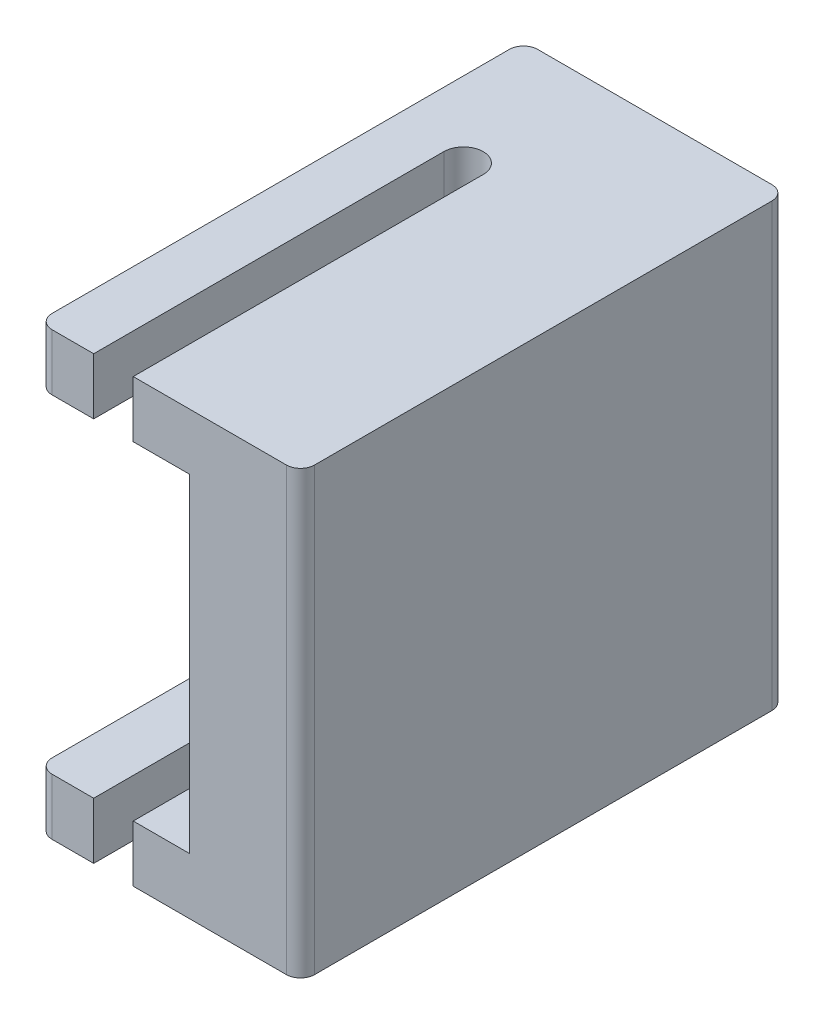
SolidWorks part; units mm, degrees
ref_plane "Front Plane" through (0, 0, 0) normal (0, 0, 1) x (1, 0, 0)
ref_plane "Top Plane" through (0, 0, 0) normal (0, 1, 0) x (1, 0, 0)
ref_plane "Right Plane" through (0, 0, 0) normal (1, 0, 0) x (0, 0, -1)
sketch "Sketch1" plane through (0, 0, 0) normal (0, 0, 1) x (1, 0, 0)
  line L0 (-46.5, 39.0875) -> (-46.5, 29.0875)
  line L1 (-46.5, 29.0875) -> (-19.625, 29.0875)
  line L2 (-19.625, 29.0875) -> (-19.625, -29.0875)
  line L3 (-19.625, -29.0875) -> (-46.5, -29.0875)
  line L4 (-46.5, -29.0875) -> (-46.5, -39.0875)
  line L5 (-46.5, -39.0875) -> (0, -39.0875)
  line L6 (0, -39.0875) -> (0, 39.0875)
  line L7 (0, 39.0875) -> (-46.5, 39.0875)
  line L8 (-29.625, 39.0875) -> (-29.625, -39.0875) construction
  line L9 (0.875, 39.0875) -> (0.875, -39.0875) construction
  point P2 (0, 0)
  point P13 (-33.125, 39.0875)
  dimension "D1" = 78.175
  dimension "D2" = 10
  dimension "D3" = 46.5
  dimension "D4" = 10
  dimension "D5" = 34
  dimension "D6" = 3.5
  dimension "D7" = 0.875
extrude "Boss-Extrude1" add sketch "Sketch1" along normal mid plane 86
sketch "Sketch2" plane through (0, 39.0875, 0) normal (0, 1, 0) x (1, 0, 0)
  line L0 (-36.625, -43) -> (-36.625, 19)
  line L1 (0, -43) -> (-46.5, -43) construction
  line L2 (-29.625, 19) -> (-29.625, -43)
  line L4 (-36.625, -43) -> (-29.625, -43)
  line L6 (0.875, 43) -> (0.875, -43) construction
  line L7 (0, -43) -> (0, 43) construction
  arc A0 (-36.625, 19) -> (-29.625, 19) centre (-33.125, 19) cw
  dimension "D1" = 3.5
  dimension "D2" = 19
  dimension "D3" = 0.875
  dimension "D4" = 34
extrude "Cut-Extrude2" cut sketch "Sketch2" against normal through all
fillet "Fillet1" radius 2.5 6 edges at (-46.5, -34.0875, -43) (-46.5, -34.0875, 43) (0, 0, -43) (-46.5, 34.0875, -43) (0, 0, 43) (-46.5, 34.0875, 43)
